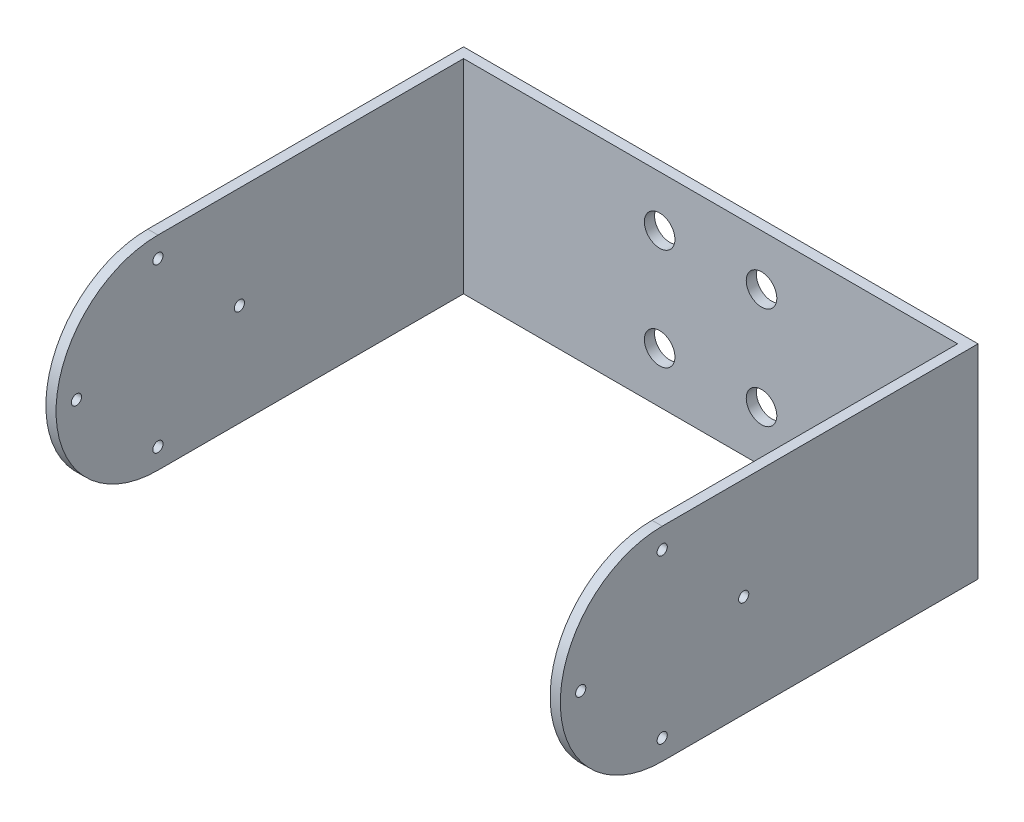
SolidWorks part; units mm, degrees
ref_plane "前视基准面" through (0, 0, 0) normal (0, 0, 1) x (1, 0, 0)
ref_plane "上视基准面" through (0, 0, 0) normal (0, 1, 0) x (1, 0, 0)
ref_plane "右视基准面" through (0, 0, 0) normal (1, 0, 0) x (0, 0, -1)
sketch "草图1" plane through (0, 0, 0) normal (0, 0, 1) x (1, 0, 0)
  line L0 (-25.25, 10) -> (25.25, -10) construction
  line L1 (-25.25, 10) -> (25.25, 10)
  line L2 (-25.25, 10) -> (-25.25, -10)
  line L3 (-25.25, -10) -> (25.25, -10)
  line L4 (25.25, 10) -> (25.25, -10)
  line L5 (-25.25, -10) -> (25.25, 10) construction
  point P4 (0, 0)
  dimension "D1" = 50.5
  dimension "D2" = 20
extrude "凸台-拉伸1" add sketch "草图1" along normal blind 1
sketch "草图2" plane through (0, 0, 1) normal (0, 0, 1) x (1, 0, 0)
  line L0 (-25.25, -10) -> (25.25, -10) construction
  line L1 (-25.25, 10) -> (-24.25, 10)
  line L2 (-25.25, 10) -> (-25.25, -10)
  line L3 (-25.25, -10) -> (-24.25, -10)
  line L4 (-24.25, 10) -> (-24.25, -10)
  line L6 (25.25, 10) -> (24.25, 10)
  line L7 (25.25, 10) -> (25.25, -10)
  line L8 (25.25, -10) -> (24.25, -10)
  line L9 (24.25, 10) -> (24.25, -10)
  dimension "D1" = 1
  dimension "D2" = 1
extrude "凸台-拉伸2" add sketch "草图2" along normal blind 40
sketch "草图3" plane through (-25.25, 0, 0) normal (-1, 0, 0) x (0, 0, 1)
  line L0 (41, -10) -> (31, -10)
  line L1 (41, -10) -> (31, -10)
  line L2 (41, -10) -> (0, -10) construction
  line L3 (41, 10) -> (31, 10)
  line L5 (41, 10) -> (0, 10) construction
  line L8 (41, -10) -> (66.2262, -10)
  line L9 (66.2262, -10) -> (66.2262, 10)
  line L10 (66.2262, 10) -> (41, 10)
  arc A0 (31, -10) -> (31, 10) centre (31, 0) ccw
  line M8 (0, -10) -> (41, -10)
  line M9 (41, -10) -> (41, 10)
  line M10 (41, 10) -> (0, 10)
extrude "切除-拉伸2" cut sketch "草图3" against normal blind 100 contours A0 M8 M9 | A0 M9 M10
sketch "草图4" plane through (25.25, 0, 0) normal (1, 0, 0) x (0, 0, -1)
  circle A0 centre (-39, 0) radius 0.5
  arc A1 (-31, 10) -> (-31, -10) centre (-31, 0) ccw construction
  circle A2 centre (-31, 8) radius 0.5
  circle A3 centre (-23, 0) radius 0.5
  circle A4 centre (-31, -8) radius 0.5
  point P2 (-31, 0)
  point P17 (-31, 0)
  dimension "D1" = 1
  dimension "D2" = 8
  dimension "D3" = 4
extrude "切除-拉伸3" cut sketch "草图4" against normal through all
sketch "草图5" plane through (0, 0, 0) normal (0, 0, -1) x (-1, 0, 0)
  line L0 (-25.25, -10) -> (-25.25, 10) construction
  line L1 (25.25, 7.5) -> (25.25, 8.5) construction
  line L2 (25.25, 10) -> (25.25, -10) construction
  circle A0 centre (-5, 5) radius 1.5
  circle A1 centre (-5, -5) radius 1.5
  circle A2 centre (5, 5) radius 1.5
  circle A3 centre (5, -5) radius 1.5
  dimension "D1" = 10
  dimension "D5" = 3
  dimension "D6" = 3
  dimension "D7" = 3
  dimension "D8" = 3
  dimension "D2" = 5
  dimension "D3" = 5
  dimension "D4" = 10
extrude "切除-拉伸4" cut sketch "草图5" against normal up to next
